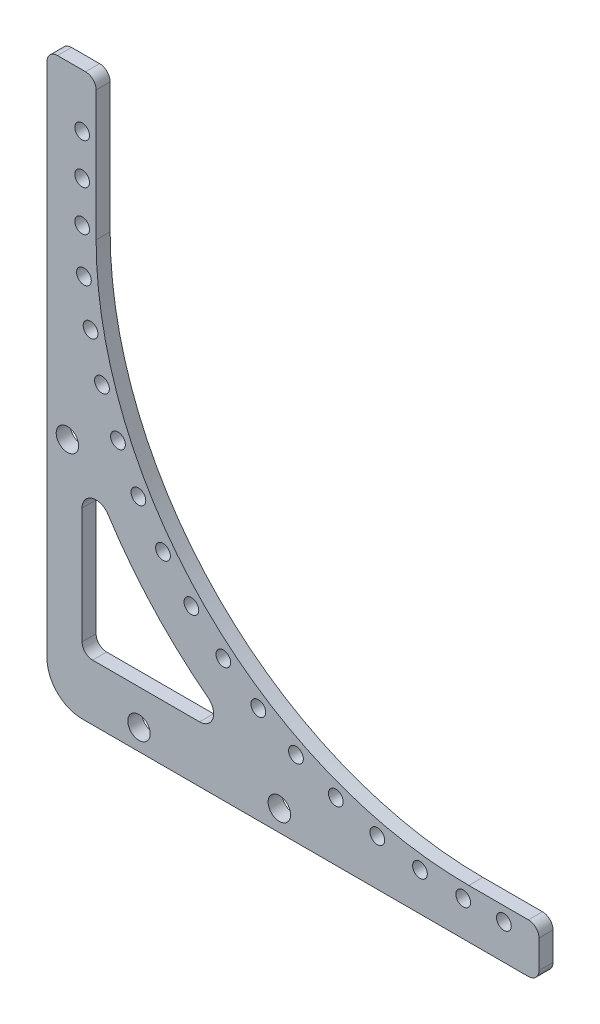
SolidWorks part; units mm, degrees
material "Thornel Mat VMA"
ref_plane "前视基准面" through (0, 0, 0) normal (0, 0, 1) x (1, 0, 0)
ref_plane "上视基准面" through (0, 0, 0) normal (0, 1, 0) x (1, 0, 0)
ref_plane "右视基准面" through (0, 0, 0) normal (1, 0, 0) x (0, 0, -1)
sketch "草图1" plane through (0, 0, 0) normal (0, 0, 1) x (1, 0, 0)
  line L0 (-53.1127, 0) -> (0, 0) construction
  line L1 (0, 0) -> (0, -53.1127) construction
  line L2 (-53.1127, 0) -> (-53.1127, 20)
  line L3 (-53.1127, 20) -> (-60.1127, 20)
  line L4 (-60.1127, 20) -> (-60.1127, -60.1127)
  line L5 (-60.1127, -60.1127) -> (10, -60.1127)
  line L6 (10, -60.1127) -> (10, -53.1127)
  line L7 (10, -53.1127) -> (0, -53.1127)
  arc A0 (-53.1127, 0) -> (0, -53.1127) centre (0, 0) ccw
  arc A1 (-9.1127, 0) -> (0, -9.1127) centre (0, 0) ccw construction
  circle A2 centre (-22, -22) radius 22 construction
  dimension "D1" = 44
  dimension "D2" = 44
  dimension "D3" = 7
  dimension "D4" = 7
  dimension "D5" = 10
  dimension "D6" = 20
extrude "凸台-拉伸1" add sketch "草图1" along normal blind 2
sketch "草图2" plane through (0, 0, 2) normal (0, 0, 1) x (1, 0, 0)
  line L4 (10, -55.1127) -> (0, -55.1127)
  line L5 (-55.1127, 0) -> (-55.1127, 20)
  line L6 (10, -55.1127) -> (0, -55.1127) construction
  line L7 (-55.1127, 0) -> (-55.1127, 20) construction
  circle A1 centre (5, -55.1127) radius 1.05
  arc A2 (-55.1127, 0) -> (0, -55.1127) centre (0, 0) ccw
  arc A3 (-55.1127, 0) -> (0, -55.1127) centre (0, 0) ccw construction
  circle A4 centre (5, -55.1127) radius 2.5 construction
  circle A5 centre (-0.8, -55.1069) radius 2.5 construction
  circle A6 centre (-0.8, -55.1069) radius 1.05 construction
  dimension "D2" = 2.1
  dimension "D3" = 5
  dimension "D4" = 5
  dimension "D5" = 0.8
  dimension "D1" = 2
extrude "切除-拉伸1" cut sketch "草图2" against normal blind 2
sketch "草图3" plane through (0, 0, 2) normal (0, 0, 1) x (1, 0, 0)
  line L0 (0, 0) -> (-0.8, -55.1069) construction
  line L1 (0, 0) -> (-6.965, -54.6708) construction
  circle A0 centre (-6.965, -54.6708) radius 2.5 construction
  circle A1 centre (-0.8, -55.1069) radius 2.5 construction
  arc A2 (-55.1127, 0) -> (0, -55.1127) centre (0, 0) ccw
  arc A3 (-55.1127, 0) -> (0, -55.1127) centre (0, 0) ccw construction
  circle A4 centre (5, -55.1127) radius 2.5 construction
  circle A5 centre (-0.8, -55.1069) radius 1.05
  circle A6 centre (5, -55.1127) radius 1.05 construction
  circle A7 centre (-6.965, -54.6708) radius 1.05
  circle A8 centre (-13.0424, -53.5472) radius 2.5 construction
  circle A9 centre (-13.0424, -53.5472) radius 1.05
  circle A10 centre (-18.9558, -51.7503) radius 2.5 construction
  circle A11 centre (-18.9558, -51.7503) radius 1.05
  circle A12 centre (-24.6308, -49.3025) radius 2.5 construction
  circle A13 centre (-24.6308, -49.3025) radius 1.05
  circle A14 centre (-29.996, -46.2347) radius 2.5 construction
  circle A15 centre (-29.996, -46.2347) radius 1.05
  circle A16 centre (-34.984, -42.5855) radius 2.5 construction
  circle A17 centre (-34.984, -42.5855) radius 1.05
  circle A18 centre (-39.5321, -38.4008) radius 2.5 construction
  circle A19 centre (-39.5321, -38.4008) radius 1.05
  circle A20 centre (-43.5831, -33.7331) radius 2.5 construction
  circle A21 centre (-43.5831, -33.7331) radius 1.05
  circle A22 centre (-47.086, -28.6413) radius 2.5 construction
  circle A23 centre (-47.086, -28.6413) radius 1.05
  circle A24 centre (-49.9967, -23.1892) radius 2.5 construction
  circle A25 centre (-49.9967, -23.1892) radius 1.05
  circle A26 centre (-52.2787, -17.4455) radius 2.5 construction
  circle A27 centre (-52.2787, -17.4455) radius 1.05
  circle A28 centre (-53.9033, -11.4825) radius 2.5 construction
  circle A29 centre (-53.9033, -11.4825) radius 1.05
  circle A30 centre (-54.85, -5.375) radius 2.5 construction
  circle A31 centre (-54.85, -5.375) radius 1.05
  circle A32 centre (-55.1069, 0.8) radius 2.5 construction
  circle A33 centre (-55.1069, 0.8) radius 1.05
  dimension "D2" = 5
  dimension "D3" = 5
  dimension "D4" = 0.8
  dimension "D6" = 6.429
  dimension "D1" = 2
  dimension "D5" = 15
extrude "切除-拉伸2" cut sketch "草图3" against normal blind 2
sketch "草图4" plane through (0, 0, 2) normal (0, 0, 1) x (1, 0, 0)
  line L0 (-55.1069, 6.6) -> (-55.1069, 0.8) construction
  circle A0 centre (-55.1069, 6.6) radius 2.5 construction
  circle A1 centre (-55.1069, 0.8) radius 2.5 construction
  circle A2 centre (-55.1069, 6.6) radius 1.05
  dimension "D1" = 5
  dimension "D2" = 5
  dimension "D3" = 0.8
  dimension "D4" = 2.1
fillet "圆角1" radius 5 1 edges at (-60.1127, -60.1127, 1)
fillet "圆角2" radius 1.5 4 edges at (-60.1127, 20, 1) (-53.1127, 20, 1) (10, -60.1127, 1) (10, -53.1127, 1)
sketch "草图5" plane through (0, 0, 2) normal (0, 0, 1) x (1, 0, 0)
  line L0 (0, 0) -> (-48.3471, -40.5681) construction
  line L1 (0, 0) -> (-57.1995, -26.6726) construction
  line L2 (0, 0) -> (-36.2, -51.6989) construction
  line L3 (-55.1127, -60.1127) -> (8.5, -60.1127) construction
  circle A1 centre (-57.1995, -26.6726) radius 1.6
  arc A2 (-63.1127, 0) -> (0, -63.1127) centre (0, 0) ccw
  arc A3 (-63.1127, 0) -> (0, -63.1127) centre (0, 0) ccw construction
  dimension "D4" = 3.2
  dimension "D2" = 30
  dimension "D3" = 40
  dimension "D1" = 10
extrude "切除-拉伸4" cut sketch "草图5" against normal blind 10
sketch "草图6" plane through (0, 0, 0) normal (0, 0, -1) x (-1, 0, 0)
  line L0 (0, 0) -> (0, -57.1127) construction
  line L1 (0, -57.1127) -> (27, -57.1127) construction
  line L2 (27, -57.1127) -> (47, -57.1127) construction
  circle A2 centre (27, -57.1127) radius 1.6
  circle A3 centre (47, -57.1127) radius 1.6
  dimension "D4" = 3.2
  dimension "D1" = 57.1127
  dimension "D2" = 27
  dimension "D3" = 20
extrude "切除-拉伸5" cut sketch "草图6" against normal blind 10
sketch "草图7" plane through (0, 0, 2) normal (0, 0, 1) x (1, 0, 0)
  line L0 (-55.1127, -52.1127) -> (-55.1127, -26.4074)
  line L1 (-55.1127, -52.1127) -> (-31.9222, -52.1127)
  line L2 (-55.1127, -60.1127) -> (8.5, -60.1127) construction
  line L3 (-60.1127, 18.5) -> (-60.1127, -55.1127) construction
  arc A2 (-61.1127, 0) -> (0, -61.1127) centre (0, 0) ccw
  arc A3 (-55.1127, -26.4074) -> (-31.9222, -52.1127) centre (0, 0) ccw
  dimension "D2" = 8
  dimension "D3" = 5
  dimension "D1" = 8
extrude "切除-拉伸6" cut sketch "草图7" against normal blind 10
fillet "圆角3" radius 2 2 edges at (-31.9222, -52.1127, 1) (-55.1127, -26.4074, 1)
fillet "圆角4" radius 1.5 1 edges at (-55.1127, -52.1127, 1)
sketch "草图10" plane through (0, 0, 2) normal (0, 0, 1) x (1, 0, 0)
  circle A0 centre (-55.1069, 0.8) radius 2.5 construction
  circle A1 centre (-55.1069, 0.8) radius 1.05 construction
  circle A2 centre (-55.1069, 0.8) radius 1.05
  circle A3 centre (-55.1069, 6.6) radius 1.05
  circle A4 centre (-55.1069, 6.6) radius 2.5 construction
  circle A5 centre (-55.1069, 12.4) radius 1.05
  circle A6 centre (-55.1069, 12.4) radius 2.5 construction
  circle A7 centre (-55.1069, 18.2) radius 1.05 construction
  circle A8 centre (-55.1069, 18.2) radius 2.5 construction
  dimension "D1" = 5
  dimension "D3" = 0.8
  dimension "D2" = 4
extrude "切除-拉伸7" cut sketch "草图10" against normal blind 10
